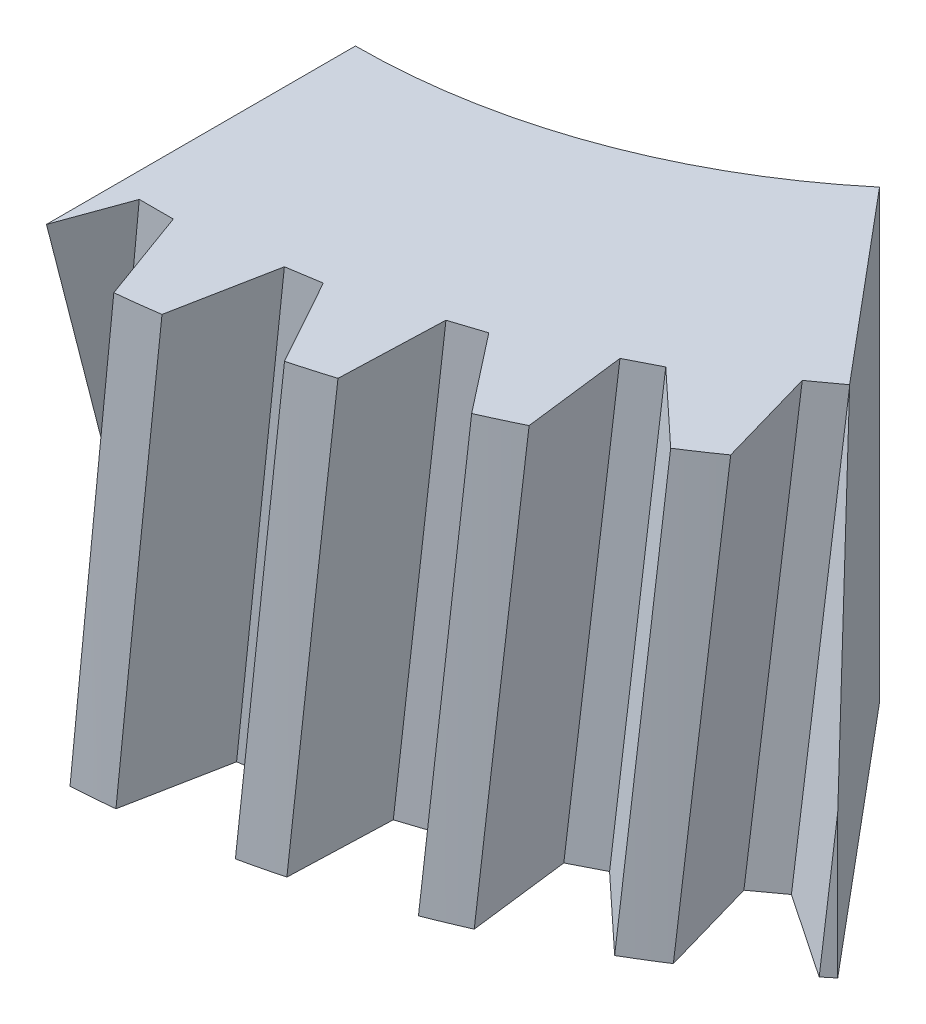
SolidWorks part; units mm, degrees
ref_plane "Спереди" through (0, 0, 0) normal (0, 0, 1) x (1, 0, 0)
ref_plane "Сверху" through (0, 0, 0) normal (0, 1, 0) x (1, 0, 0)
ref_plane "Справа" through (0, 0, 0) normal (1, 0, 0) x (0, 0, -1)
sketch "Эскиз1" plane through (0, 0, 0) normal (0, 1, 0) x (1, 0, 0)
  circle A0 centre (0, 0) radius 31.5
  circle A1 centre (0, 0) radius 20.1
  dimension "D1" = 40.2
  dimension "63" = 63
extrude "Бобышка-Вытянуть1" add sketch "Эскиз1" along normal blind 15
sketch "Эскиз7" plane through (0, 0, 0) normal (0, 1, 0) x (1, 0, 0)
  line L0 (0, 0) -> (32, 0) construction
  line L1 (28.2, -0.5719) -> (28.2, 0.5719)
  line L2 (32, -1.955) -> (32, 1.955)
  line L3 (28.2, 0.5719) -> (32, 1.955)
  line L4 (28.2, -0.5719) -> (32, -1.955)
  line L5 (30, 1.2271) -> (30, -1.2271) construction
  dimension "D1" = 32
  dimension "D2" = 28.2
  dimension "D3" = 20
  dimension "D4" = 3.91
  dimension "D5" = 30
ref_plane "Плоскость6" through (30, 0, 0) normal (1, 0, 0) x (0, 0, -1)
sketch "Эскиз8" plane through (30, 0, 0) normal (1, 0, 0) x (0, 0, -1)
  line L0 (0, 0) -> (0, 15) construction
  line L1 (31.5, 15) -> (-31.5, 15) construction
  line L2 (0, 0) -> (1.6102, 17.1938)
  dimension "D1" = 5.35
sweep "Вырез-По траектории4" cut profiles "Эскиз7" path "Эскиз8"
pattern_circular "Круговой массив4" count 40 over 360 about axis through (0, 0, 0) along (0, 1, 0) of "Вырез-По траектории4"
sketch "Эскиз9" plane through (0, 15, 0) normal (0, 1, 0) x (1, 0, 0)
  line L0 (0, 0) -> (0, -31.5)
  line L1 (0, 0) -> (20.2478, -24.1304)
  arc A2 (-1.8206, -31.4473) -> (-0.3675, -31.4979) centre (0, 0) ccw construction
  arc A3 (20.9493, -23.524) -> (22.0125, -22.5322) centre (0, 0) ccw construction
  arc A4 (0, -31.5) -> (20.2478, -24.1304) centre (0, 0) ccw
  dimension "D1" = 40
extrude "Вырез-Вытянуть1" cut sketch "Эскиз9" against normal through all flip side to cut
